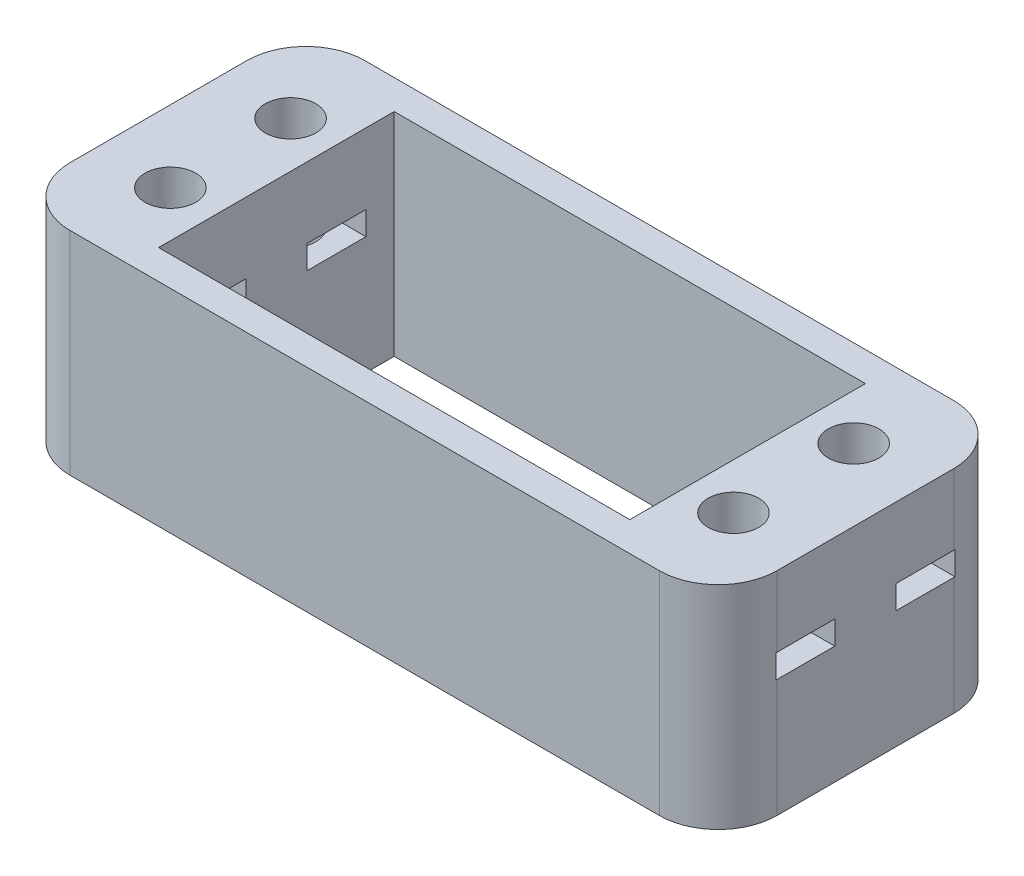
SolidWorks part; units mm, degrees
ref_plane "Plan de face" through (0, 0, 0) normal (0, 0, 1) x (1, 0, 0)
ref_plane "Plan de dessus" through (0, 0, 0) normal (0, 1, 0) x (1, 0, 0)
ref_plane "Plan de droite" through (0, 0, 0) normal (1, 0, 0) x (0, 0, -1)
sketch "Esquisse1" plane through (0, 0, 0) normal (0, 0, 1) x (1, 0, 0)
  line L1 (-30, -9) -> (30, -9)
  line L2 (-30, -9) -> (-30, 9)
  line L3 (-30, 9) -> (30, 9)
  line L4 (30, -9) -> (30, 9)
  line L5 (-30, -9) -> (30, 9) construction
  line L6 (-30, 9) -> (30, -9) construction
  point P0 (0, 0)
  dimension "D1" = 60
  dimension "D2" = 18
extrude "Boss.-Extru.1" add sketch "Esquisse1" along normal blind 25
sketch "Esquisse2" plane through (0, -9, 0) normal (0, -1, 0) x (1, 0, 0)
  line L0 (30, 0) -> (-30, 25) construction
  line L2 (20, 22.5) -> (-20, 22.5)
  line L3 (20, 22.5) -> (20, 2.5)
  line L4 (20, 2.5) -> (-20, 2.5)
  line L5 (-20, 22.5) -> (-20, 2.5)
  line L6 (20, 22.5) -> (-20, 2.5) construction
  line L7 (20, 2.5) -> (-20, 22.5) construction
  point P4 (0, 12.5)
  dimension "D1" = 40
  dimension "D2" = 20
extrude "Enlèv. mat.-Extru.1" cut sketch "Esquisse2" against normal blind 30
fillet "Congé1" radius 5 4 edges at (30, 0, 25) (30, 0, 0) (-30, 0, 0) (-30, 0, 25)
sketch "Esquisse3" plane through (0, -9, 0) normal (0, -1, 0) x (-1, 0, 0)
  circle A0 centre (23.9, -17.6) radius 2.15
  circle A1 centre (23.9, -7.4) radius 2.15
  circle A2 centre (-23.9, -7.4) radius 2.15
  circle A3 centre (-23.9, -17.6) radius 2.15
  dimension "D1" = 4.3
  dimension "D2" = 4.3
  dimension "D3" = 4.3
  dimension "D4" = 4.3
extrude "Enlèv. mat.-Extru.2" cut sketch "Esquisse3" against normal blind 30
sketch "Esquisse4" plane through (-30, 0, 0) normal (-1, 0, 0) x (0, 0, 1)
  line L0 (9.55, 9) -> (5.25, 9) construction
  line L1 (7.4, 9) -> (7.4, -9) construction
  line L2 (20, -9) -> (5, -9) construction
  line L3 (12.5, 9) -> (12.5, -9) construction
  line L4 (4.9, 1) -> (9.9, 1)
  line L5 (4.9, 1) -> (4.9, 3)
  line L6 (4.9, 3) -> (9.9, 3)
  line L7 (9.9, 1) -> (9.9, 3)
  line L8 (4.9, 1) -> (9.9, 3) construction
  line L9 (4.9, 3) -> (9.9, 1) construction
  line L10 (20, 9) -> (5, 9) construction
  line L11 (20.1, 1) -> (20.1, 3)
  line L12 (20.1, 1) -> (15.1, 1)
  line L13 (15.1, 1) -> (15.1, 3)
  line L14 (20.1, 3) -> (15.1, 3)
  point P8 (7.4, 2)
  dimension "D1" = 7
  dimension "D2" = 5
  dimension "D3" = 2
extrude "Enlèv. mat.-Extru.3" cut sketch "Esquisse4" against normal blind 80 and the other way through all
